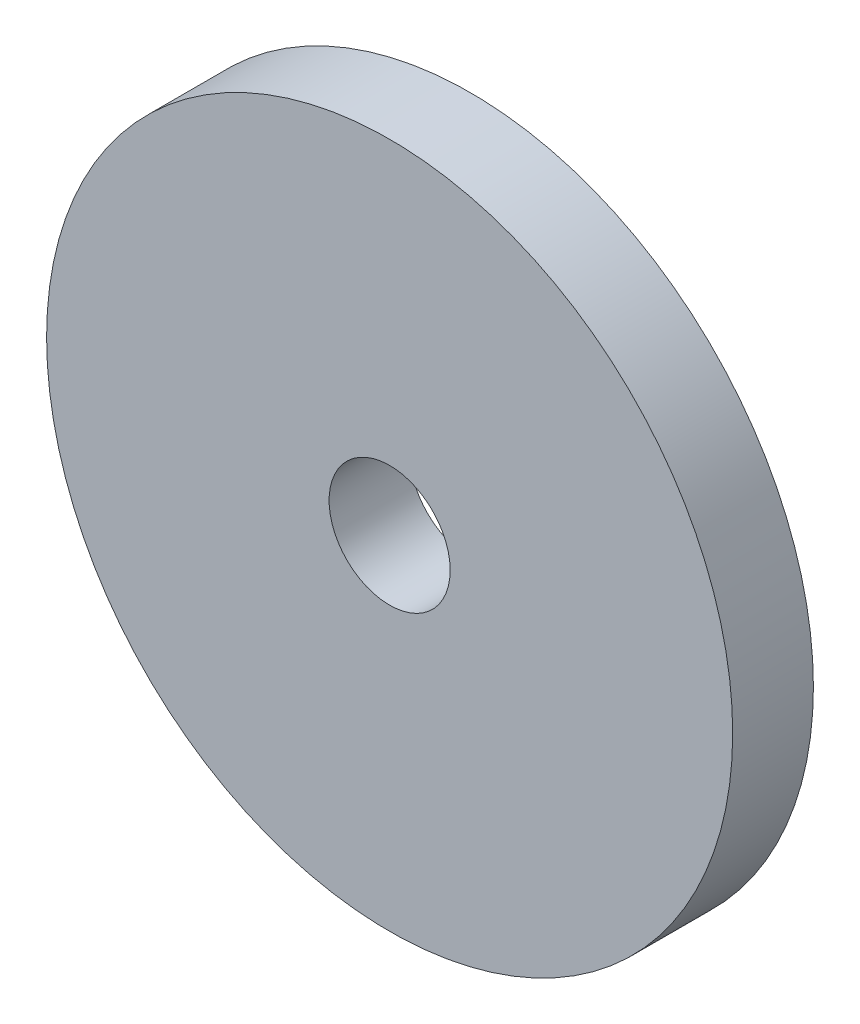
SolidWorks part; units mm, degrees
material "Beech"
ref_plane "Front Plane" through (0, 0, 0) normal (0, 0, 1) x (1, 0, 0)
ref_plane "Top Plane" through (0, 0, 0) normal (0, 1, 0) x (1, 0, 0)
ref_plane "Right Plane" through (0, 0, 0) normal (1, 0, 0) x (0, 0, -1)
sketch "Sketch1" plane through (0, 0, 0) normal (0, 0, 1) x (1, 0, 0)
  line L0 (8, 20) -> (31.5, 20) construction
  line L1 (39.5, 12) -> (31.5, 20) construction
  line L2 (39.5, 12) -> (39.5, 8) construction
  line L3 (31.5, 0) -> (39.5, 8) construction
  line L4 (31.5, 0) -> (8, 0) construction
  line L5 (0, 8) -> (0, 12) construction
  line L6 (8, 0) -> (0, 8) construction
  line L7 (8, 20) -> (0, 12) construction
  line L8 (6, 8) -> (6, 12) construction
  line L9 (6, 12) -> (13.75, 12) construction
  line L10 (13.75, 12) -> (13.75, 8) construction
  line L11 (13.75, 8) -> (6, 8) construction
  line L12 (25.75, 8) -> (25.75, 12) construction
  line L13 (25.75, 12) -> (33.5, 12) construction
  line L14 (33.5, 12) -> (33.5, 8) construction
  line L15 (33.5, 8) -> (25.75, 8) construction
  circle A0 centre (19.75, 10) radius 3
  circle A1 centre (18, 17) radius 0.75 construction
  circle A2 centre (21.5, 17) radius 0.75 construction
  circle A3 centre (18, 3.5) radius 0.5 construction
  circle A4 centre (21.5, 3.5) radius 0.5 construction
  circle A5 centre (19.75, 10) radius 17
  dimension "D1" = 34
extrude "Boss-Extrude1" add sketch "Sketch1" along normal blind 4
